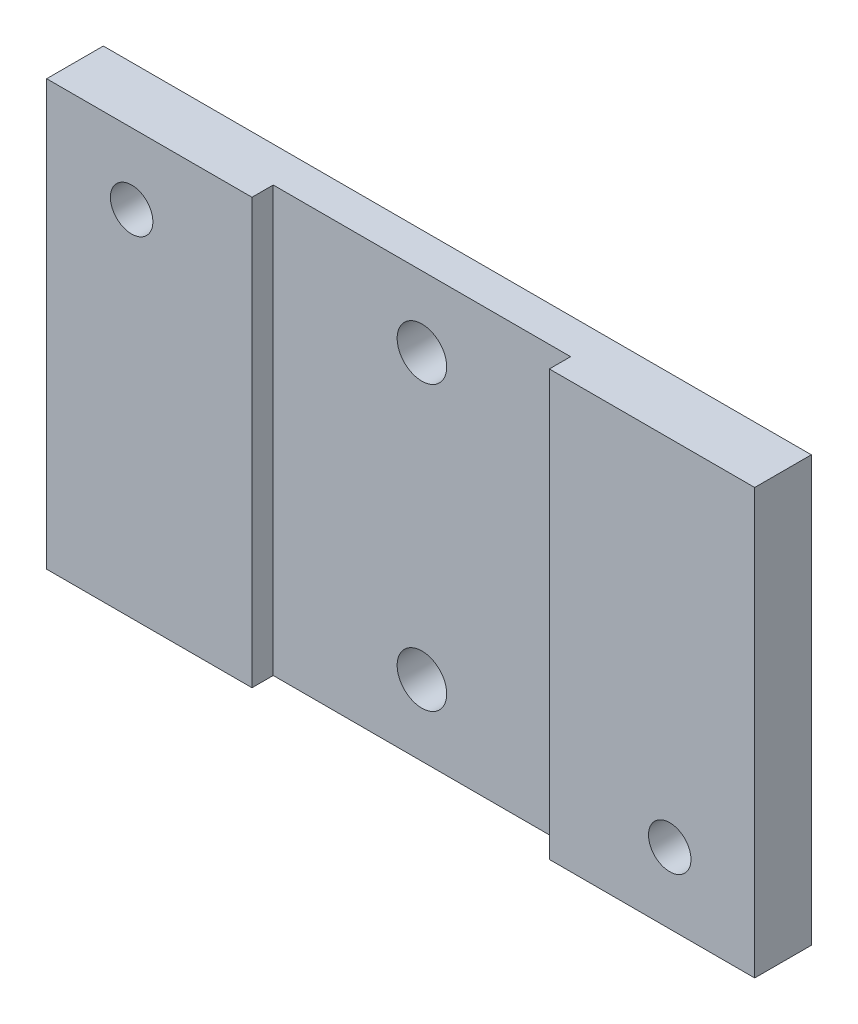
SolidWorks part; units mm, degrees
ref_plane "Front Plane" through (0, 0, 0) normal (0, 0, 1) x (1, 0, 0)
ref_plane "Top Plane" through (0, 0, 0) normal (0, 1, 0) x (1, 0, 0)
ref_plane "Right Plane" through (0, 0, 0) normal (1, 0, 0) x (0, 0, -1)
sketch "Sketch1" plane through (0, 0, 0) normal (0, 0, 1) x (1, 0, 0)
  line L1 (0, 0) -> (50, 0)
  line L2 (0, 0) -> (0, 30)
  line L3 (0, 30) -> (50, 30)
  line L4 (50, 0) -> (50, 30)
  circle A0 centre (6, 25) radius 1.5
  circle A1 centre (44, 5) radius 1.5
  dimension "D3" = 38
  dimension "D4" = 20
  dimension "D5" = 3
  dimension "D6" = 3
  dimension "D7" = 5
  dimension "D1" = 30
  dimension "D2" = 50
  dimension "D8" = 6
extrude "Boss-Extrude1" add sketch "Sketch1" along normal blind 4
sketch "Sketch2" plane through (0, 0, 4) normal (0, 0, 1) x (1, 0, 0)
  line L0 (50, 30) -> (0, 30) construction
  line L1 (14.5, 30) -> (35.5, 30)
  line L2 (14.5, 30) -> (14.5, 0)
  line L3 (14.5, 0) -> (35.5, 0)
  line L4 (35.5, 30) -> (35.5, 0)
  line L5 (0, 0) -> (50, 0) construction
  line L6 (0, 30) -> (0, 0) construction
  dimension "D1" = 21
  dimension "D2" = 14.5
extrude "Cut-Extrude1" cut sketch "Sketch2" against normal blind 1.5
sketch "Sketch3" plane through (0, 0, 2.5) normal (0, 0, 1) x (1, 0, 0)
  line L0 (0, 30) -> (0, 0) construction
  line L1 (35.5, 30) -> (14.5, 30) construction
  line L2 (14.5, 0) -> (35.5, 0) construction
  circle A0 centre (25, 25) radius 1.75
  circle A1 centre (25, 5) radius 1.75
  dimension "D1" = 3.5
  dimension "D2" = 3.5
  dimension "D3" = 25
  dimension "D4" = 25
  dimension "D5" = 5
  dimension "D6" = 5
extrude "Cut-Extrude2" cut sketch "Sketch3" against normal blind 5
